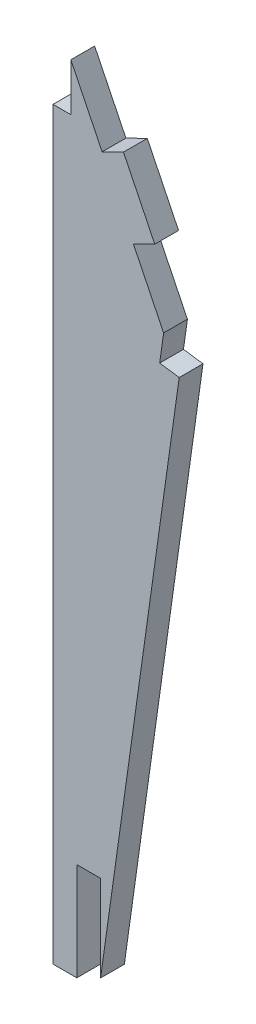
SolidWorks part; units mm, degrees
ref_plane "前视基准面" through (0, 0, 0) normal (0, 0, 1) x (1, 0, 0)
ref_plane "上视基准面" through (0, 0, 0) normal (0, 1, 0) x (1, 0, 0)
ref_plane "右视基准面" through (0, 0, 0) normal (1, 0, 0) x (0, 0, -1)
sketch "草图1" plane through (0, 0, 0) normal (0, 0, 1) x (1, 0, 0)
  line L0 (17.3435, 74.7028) -> (17.3435, 70.7028)
  line L1 (17.3435, 70.7028) -> (15.8435, 70.7028)
  line L2 (15.8435, 70.7028) -> (15.8435, 8.0801)
  line L3 (15.8435, 8.0801) -> (17.8435, 8.0801)
  line L4 (17.8435, 8.0801) -> (17.8435, 16.3301)
  line L5 (17.8435, 16.3301) -> (19.8435, 16.3301)
  line L6 (19.8435, 16.3301) -> (19.8435, 9.0685)
  line L7 (19.8435, 9.0685) -> (26.4564, 56.1143)
  line L8 (26.4564, 56.1143) -> (24.8148, 56.3455)
  line L9 (24.8148, 56.3455) -> (25.1469, 58.7034)
  line L10 (17.3435, 74.7028) -> (19.9737, 69.31)
  line L11 (19.9737, 69.31) -> (21.7713, 70.1868)
  line L12 (21.7713, 70.1868) -> (24.4015, 64.794)
  line L13 (24.4015, 64.794) -> (22.6039, 63.9173)
  line L14 (22.6039, 63.9173) -> (25.1469, 58.7034)
extrude "凸台-拉伸1" add sketch "草图1" along normal blind 2
